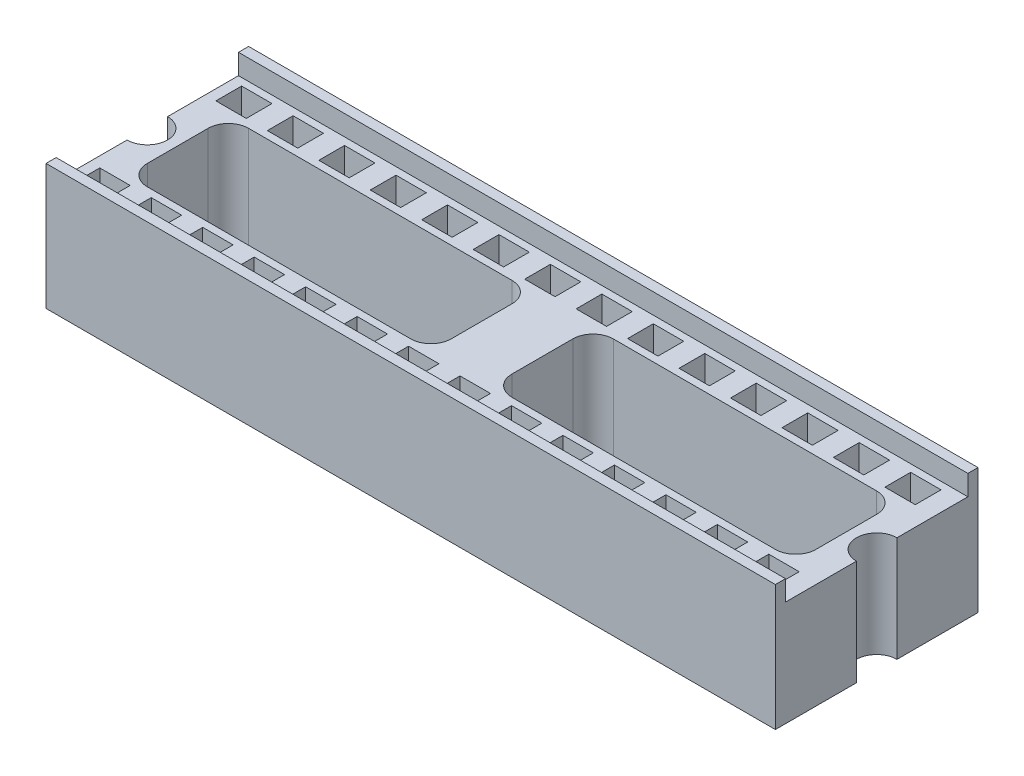
SolidWorks part; units mm, degrees
ref_plane "Plan de face" through (0, 0, 0) normal (0, 0, 1) x (1, 0, 0)
ref_plane "Plan de dessus" through (0, 0, 0) normal (0, 1, 0) x (1, 0, 0)
ref_plane "Plan de droite" through (0, 0, 0) normal (1, 0, 0) x (0, 0, -1)
sketch "Esquisse2" plane through (0, 0, 0) normal (0, 1, 0) x (1, 0, 0)
  line L0 (0, 5) -> (0, -5) construction
  line L1 (-18, -5) -> (18, -5)
  line L2 (-18, -5) -> (-18, -1)
  line L3 (-18, 5) -> (18, 5)
  line L4 (18, -5) -> (18, -1)
  line L5 (-18, -5) -> (18, 5) construction
  line L6 (-18, 5) -> (18, -5) construction
  line L7 (-9, 5) -> (-9, -5) construction
  line L8 (1.5, -1.5) -> (1.5, 1.5)
  line L9 (-15.5, -2.5) -> (-2.5, -2.5)
  line L10 (-16.5, -1.5) -> (-16.5, 1.5)
  line L11 (-15.5, 2.5) -> (-2.5, 2.5)
  line L12 (-1.5, -1.5) -> (-1.5, 1.5)
  line L13 (-16.5, -2.5) -> (-1.5, 2.5) construction
  line L14 (-16.5, 2.5) -> (-1.5, -2.5) construction
  line L15 (15.5, -2.5) -> (2.5, -2.5)
  line L16 (16.5, -1.5) -> (16.5, 1.5)
  line L17 (15.5, 2.5) -> (2.5, 2.5)
  line L18 (-18, 1) -> (-18, 5)
  line L19 (18, 1) -> (18, 5)
  arc A0 (-18, 1) -> (-18, -1) centre (-18, 0) cw
  arc A1 (18, 1) -> (18, -1) centre (18, 0) ccw
  arc A2 (-15.5, -2.5) -> (-16.5, -1.5) centre (-15.5, -1.5) cw
  arc A3 (-2.5, -2.5) -> (-1.5, -1.5) centre (-2.5, -1.5) ccw
  arc A4 (-2.5, 2.5) -> (-1.5, 1.5) centre (-2.5, 1.5) cw
  arc A5 (-16.5, 1.5) -> (-15.5, 2.5) centre (-15.5, 1.5) cw
  arc A6 (2.5, 2.5) -> (1.5, 1.5) centre (2.5, 1.5) ccw
  arc A7 (2.5, -2.5) -> (1.5, -1.5) centre (2.5, -1.5) cw
  arc A8 (15.5, -2.5) -> (16.5, -1.5) centre (15.5, -1.5) ccw
  arc A9 (16.5, 1.5) -> (15.5, 2.5) centre (15.5, 1.5) ccw
  point P0 (0, 0)
  point P16 (-9, 0)
  dimension "D3" = 1
  dimension "D4" = 9
  dimension "D7" = 1
  dimension "D1" = 36
  dimension "D2" = 10
  dimension "D5" = 15
  dimension "D6" = 5
extrude "Boss.-Extru.1" add sketch "Esquisse2" against normal blind 6.2
sketch "Esquisse4" plane through (18, 0, 0) normal (1, 0, 0) x (0, 0, -1)
  line L0 (-4.5, 0.6184) -> (-4.5, -1)
  line L1 (-4.5, -1) -> (4.5, -1)
  line L2 (4.5, -1) -> (4.5, 0.6184)
  line L3 (4.5, 0.6184) -> (-4.5, 0.6184)
  line L4 (-5, -6.2) -> (-5, 0) construction
  line L6 (1, 0) -> (5, 0) construction
  dimension "D1" = 9
  dimension "D2" = 0.5
  dimension "D3" = 1
extrude "Enlèv. mat.-Extru.1" cut sketch "Esquisse4" against normal blind 40.6
sketch "Esquisse5" plane through (0, -1, 0) normal (0, 1, 0) x (1, 0, 0)
  line L0 (-18, 4.5) -> (-18, 1) construction
  line L1 (-17.48, 4.135) -> (-15.98, 4.135)
  line L2 (-17.48, 4.135) -> (-17.48, 2.865)
  line L3 (-17.48, 2.865) -> (-15.98, 2.865)
  line L4 (-15.98, 4.135) -> (-15.98, 2.865)
  line L5 (-17.48, 4.135) -> (-15.98, 2.865) construction
  line L6 (-17.48, 2.865) -> (-15.98, 4.135) construction
  line L7 (-18, 4.5) -> (18, 4.5) construction
  line L8 (-13.44, 4.135) -> (-13.44, 2.865)
  line L9 (-14.94, 2.865) -> (-13.44, 2.865)
  line L10 (-14.94, 4.135) -> (-14.94, 2.865)
  line L11 (-14.94, 4.135) -> (-13.44, 4.135)
  line L12 (-10.9, 4.135) -> (-10.9, 2.865)
  line L13 (-12.4, 2.865) -> (-10.9, 2.865)
  line L14 (-12.4, 4.135) -> (-12.4, 2.865)
  line L15 (-12.4, 4.135) -> (-10.9, 4.135)
  line L16 (-8.36, 4.135) -> (-8.36, 2.865)
  line L17 (-9.86, 2.865) -> (-8.36, 2.865)
  line L18 (-9.86, 4.135) -> (-9.86, 2.865)
  line L19 (-9.86, 4.135) -> (-8.36, 4.135)
  line L20 (-5.82, 4.135) -> (-5.82, 2.865)
  line L21 (-7.32, 2.865) -> (-5.82, 2.865)
  line L22 (-7.32, 4.135) -> (-7.32, 2.865)
  line L23 (-7.32, 4.135) -> (-5.82, 4.135)
  line L24 (-3.28, 4.135) -> (-3.28, 2.865)
  line L25 (-4.78, 2.865) -> (-3.28, 2.865)
  line L26 (-4.78, 4.135) -> (-4.78, 2.865)
  line L27 (-4.78, 4.135) -> (-3.28, 4.135)
  line L28 (-0.74, 4.135) -> (-0.74, 2.865)
  line L29 (-2.24, 2.865) -> (-0.74, 2.865)
  line L30 (-2.24, 4.135) -> (-2.24, 2.865)
  line L31 (-2.24, 4.135) -> (-0.74, 4.135)
  line L32 (1.8, 4.135) -> (1.8, 2.865)
  line L33 (0.3, 2.865) -> (1.8, 2.865)
  line L34 (0.3, 4.135) -> (0.3, 2.865)
  line L35 (0.3, 4.135) -> (1.8, 4.135)
  line L36 (4.34, 4.135) -> (4.34, 2.865)
  line L37 (2.84, 2.865) -> (4.34, 2.865)
  line L38 (2.84, 4.135) -> (2.84, 2.865)
  line L39 (2.84, 4.135) -> (4.34, 4.135)
  line L40 (6.88, 4.135) -> (6.88, 2.865)
  line L41 (5.38, 2.865) -> (6.88, 2.865)
  line L42 (5.38, 4.135) -> (5.38, 2.865)
  line L43 (5.38, 4.135) -> (6.88, 4.135)
  line L44 (9.42, 4.135) -> (9.42, 2.865)
  line L45 (7.92, 2.865) -> (9.42, 2.865)
  line L46 (7.92, 4.135) -> (7.92, 2.865)
  line L47 (7.92, 4.135) -> (9.42, 4.135)
  line L48 (11.96, 4.135) -> (11.96, 2.865)
  line L49 (10.46, 2.865) -> (11.96, 2.865)
  line L50 (10.46, 4.135) -> (10.46, 2.865)
  line L51 (10.46, 4.135) -> (11.96, 4.135)
  line L52 (14.5, 4.135) -> (14.5, 2.865)
  line L53 (13, 2.865) -> (14.5, 2.865)
  line L54 (13, 4.135) -> (13, 2.865)
  line L55 (13, 4.135) -> (14.5, 4.135)
  line L56 (17.04, 4.135) -> (17.04, 2.865)
  line L57 (15.54, 2.865) -> (17.04, 2.865)
  line L58 (15.54, 4.135) -> (15.54, 2.865)
  line L59 (15.54, 4.135) -> (17.04, 4.135)
  point P0 (-16.73, 3.5)
  dimension "D1" = 1.27
  dimension "D2" = 1
  dimension "D3" = 1.27
  dimension "D4" = 1.5
  dimension "D5" = 14
extrude "Enlèv. mat.-Extru.2" cut sketch "Esquisse5" against normal blind 4.5
mirror "Symétrie1" about plane through (0, 0, 0) normal (0, 0, 1) of "Enlèv. mat.-Extru.2"
